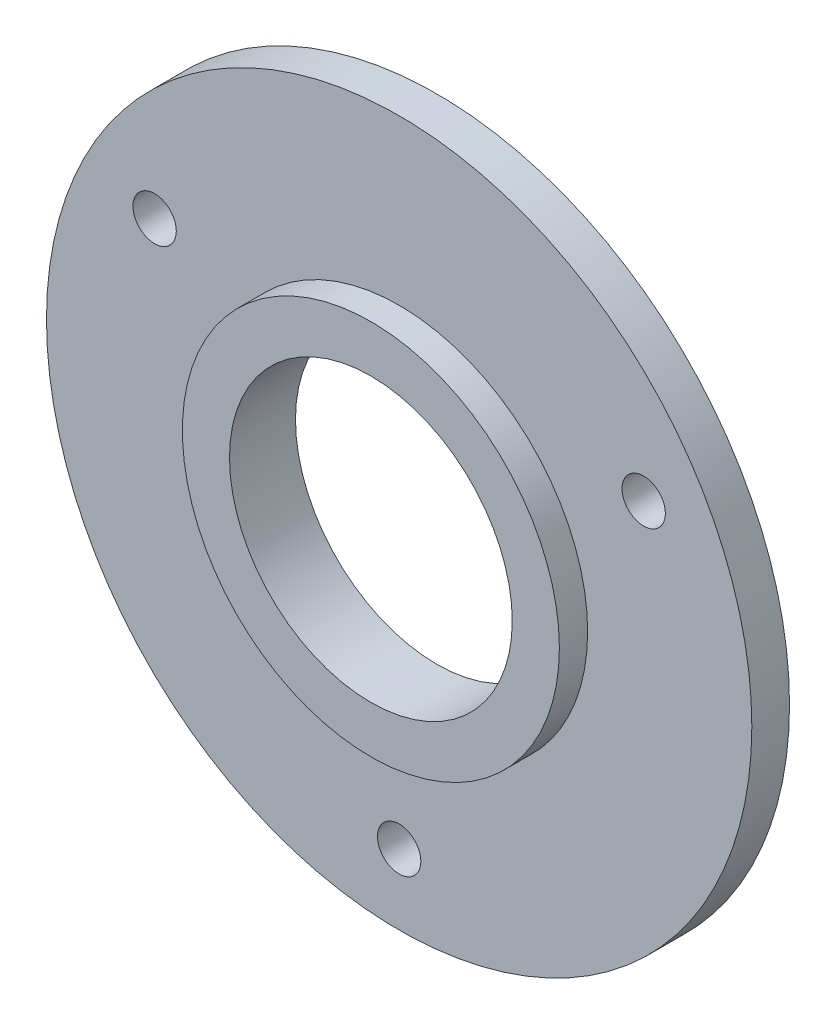
SolidWorks part; units mm, degrees
ref_plane "Front" through (0, 0, 0) normal (0, 0, 1) x (1, 0, 0)
ref_plane "Top" through (0, 0, 0) normal (0, 1, 0) x (1, 0, 0)
ref_plane "Right" through (0, 0, 0) normal (1, 0, 0) x (0, 0, -1)
sketch "Sketch1" plane through (0, 0, 0) normal (0, 0, 1) x (1, 0, 0)
  line L0 (0, 0) -> (0, -14.98) construction
  circle A0 centre (0, 0) radius 18.71
  circle A1 centre (0, -14.98) radius 1.15
  circle A2 centre (-12.9731, 7.49) radius 1.15
  circle A3 centre (12.9731, 7.49) radius 1.15
  circle A4 centre (0, 0) radius 7.5
  dimension "D1" = 37.42
  dimension "D2" = 2.3
  dimension "D5" = 15
  dimension "D4" = 14.98
  dimension "D3" = 3
extrude "Boss-Extrude1" add sketch "Sketch1" along normal blind 2
sketch "Sketch2" plane through (0, 0, 2) normal (0, 0, 1) x (1, 0, 0)
  circle A0 centre (0, 0) radius 10
  circle A1 centre (0, 0) radius 7.5 construction
  circle A2 centre (0, 0) radius 7.5
  dimension "D1" = 20
extrude "Boss-Extrude2" add sketch "Sketch2" along normal blind 1.5
